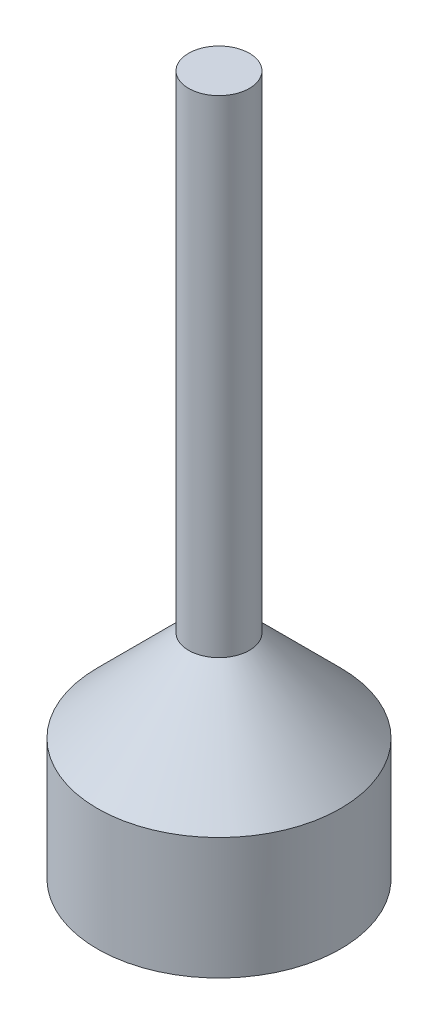
SolidWorks part; units mm, degrees
material "6061 合金"
ref_plane "前视基准面" through (0, 0, 0) normal (0, 0, 1) x (1, 0, 0)
ref_plane "上视基准面" through (0, 0, 0) normal (0, 1, 0) x (1, 0, 0)
ref_plane "右视基准面" through (0, 0, 0) normal (1, 0, 0) x (0, 0, -1)
sketch "草图1" plane through (0, 0, 0) normal (0, 0, 1) x (1, 0, 0)
  line L0 (0, 0) -> (-20, 0)
  line L1 (-20, 0) -> (-20, 20)
  line L2 (-20, 20) -> (-5, 35)
  line L3 (-5, 35) -> (-5, 115)
  line L4 (-5, 115) -> (0, 115)
  line L5 (0, 115) -> (0, 0)
  dimension "D1" = 5
  dimension "D2" = 20
  dimension "D3" = 80
  dimension "D4" = 115
  dimension "D5" = 45
revolve "旋转1" add sketch "草图1" angle 360 about L5
